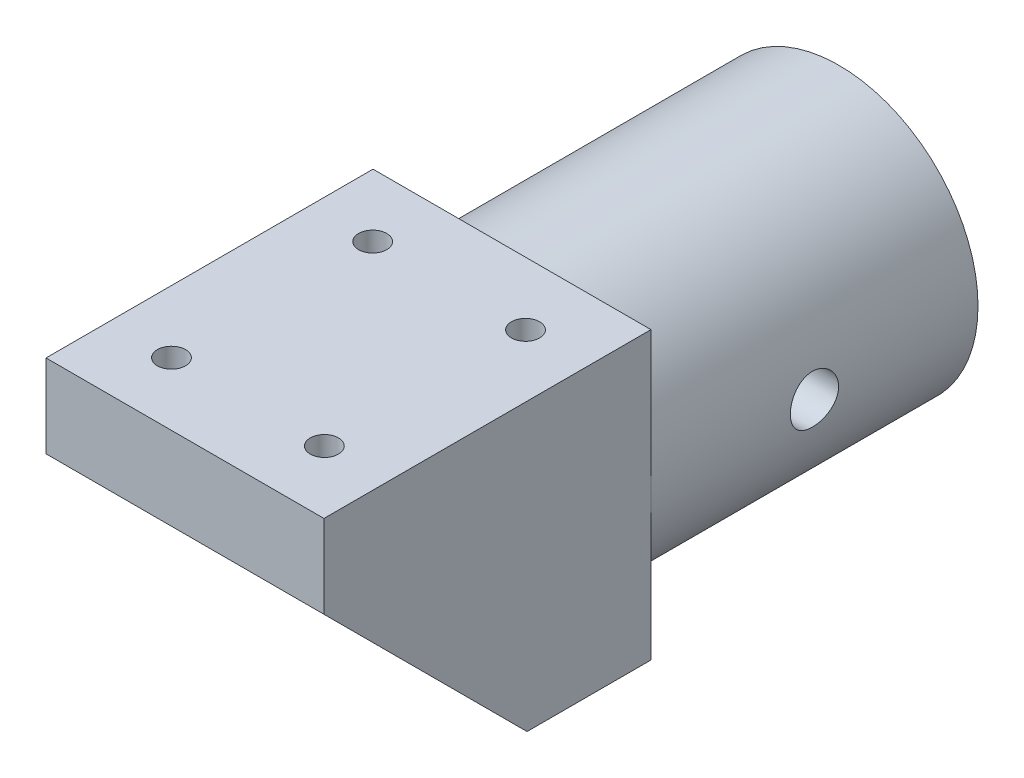
SolidWorks part; units mm, degrees
ref_plane "Front Plane" through (0, 0, 0) normal (0, 0, 1) x (1, 0, 0)
ref_plane "Top Plane" through (0, 0, 0) normal (0, 1, 0) x (1, 0, 0)
ref_plane "Right Plane" through (0, 0, 0) normal (1, 0, 0) x (0, 0, -1)
sketch "Sketch1" plane through (0, 0, 0) normal (0, 0, 1) x (1, 0, 0)
  circle A0 centre (0, 0) radius 9.652
  circle A1 centre (0, 0) radius 17.272
  dimension "D1" = 7.62
  dimension "D2" = 19.304
extrude "Boss-Extrude1" add sketch "Sketch1" along normal blind 40.64
sketch "Sketch3" plane through (0, 0, 0) normal (0, 1, 0) x (1, 0, 0)
  line L1 (-17.272, -40.64) -> (17.272, -40.64)
  line L2 (-17.272, -40.64) -> (-17.272, -81.28)
  line L3 (-17.272, -81.28) -> (17.272, -81.28)
  line L4 (17.272, -40.64) -> (17.272, -81.28)
  dimension "D1" = 34.544
  dimension "D2" = 40.64
extrude "Boss-Extrude2" add sketch "Sketch3" along normal blind 17.78 and the other way blind 17.78
chamfer "Chamfer1" distance 25.24 angle 45 1 edges at (0, -17.78, 81.28)
sketch "Sketch5" plane through (0, 17.78, 0) normal (0, 1, 0) x (1, 0, 0)
  line L0 (0, -40.64) -> (0, -81.28) construction
  line L1 (-9.5, -48.46) -> (9.5, -48.46) construction
  line L2 (-9.5, -48.46) -> (-9.5, -73.46) construction
  line L3 (-9.5, -73.46) -> (9.5, -73.46) construction
  line L4 (9.5, -48.46) -> (9.5, -73.46) construction
  line L5 (-9.5, -48.46) -> (9.5, -73.46) construction
  line L6 (-9.5, -73.46) -> (9.5, -48.46) construction
  line L7 (17.272, -40.64) -> (-17.272, -40.64) construction
  line L8 (-17.272, -81.28) -> (17.272, -81.28) construction
  line L9 (-17.272, -60.96) -> (17.272, -60.96) construction
  line L10 (-17.272, -40.64) -> (-17.272, -81.28) construction
  line L11 (17.272, -81.28) -> (17.272, -40.64) construction
  circle A0 centre (-9.5, -48.46) radius 1.75
  circle A1 centre (9.5, -48.46) radius 1.75
  circle A2 centre (9.5, -73.46) radius 1.75
  circle A3 centre (-9.5, -73.46) radius 1.75
  point P0 (0, -60.96)
  dimension "D3" = 3.5
  dimension "D4" = 3.5
  dimension "D5" = 3.5
  dimension "D6" = 3.5
  dimension "D1" = 19
  dimension "D2" = 25
extrude "Cut-Extrude2" cut sketch "Sketch5" against normal blind 40.64
sketch "Sketch7" plane through (0, -17.78, 0) normal (0, -1, 0) x (1, 0, 0)
  circle A0 centre (-9.5, 73.46) radius 6.35
  circle A1 centre (9.5, 73.46) radius 6.35
  circle A2 centre (-9.5, 48.46) radius 6.35
  circle A3 centre (9.5, 48.46) radius 6.35
  dimension "D1" = 12.7
  dimension "D2" = 12.7
  dimension "D3" = 12.7
  dimension "D4" = 12.7
extrude "Cut-Extrude6" cut sketch "Sketch7" against normal blind 30.48
sketch "Sketch8" plane through (0, 0, 0) normal (1, 0, 0) x (0, 0, -1)
  line L0 (-20.32, 17.272) -> (-20.32, -17.272) construction
  line L1 (0, 17.272) -> (-40.64, 17.272) construction
  line L2 (-40.64, -17.272) -> (0, -17.272) construction
  circle A0 centre (-20.32, 0) radius 3
extrude "Cut-Extrude7" cut sketch "Sketch8" against normal blind 30.48 and the other way blind 30.48
